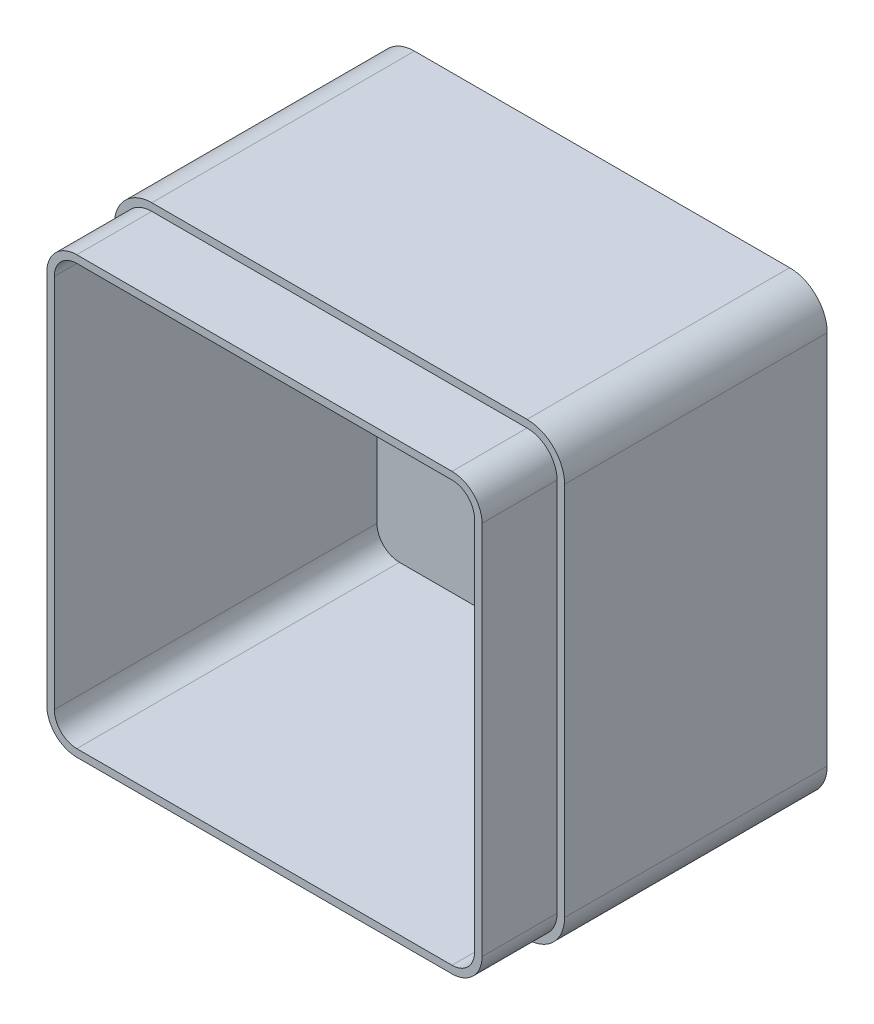
SolidWorks part; units mm, degrees
ref_plane "Front Plane" through (0, 0, 0) normal (0, 0, 1) x (1, 0, 0)
ref_plane "Top Plane" through (0, 0, 0) normal (0, 1, 0) x (1, 0, 0)
ref_plane "Right Plane" through (0, 0, 0) normal (1, 0, 0) x (0, 0, -1)
sketch "Sketch1" plane through (0, 0, 0) normal (0, 0, 1) x (1, 0, 0)
  line L1 (0, 0) -> (120, 0)
  line L2 (0, 0) -> (0, 120)
  line L3 (0, 120) -> (120, 120)
  line L4 (120, 0) -> (120, 120)
  dimension "D1" = 120
  dimension "D2" = 120
extrude "Boss-Extrude1" add sketch "Sketch1" along normal blind 90
fillet "Fillet1" radius 10 4 edges at (0, 120, 45) (0, 0, 45) (120, 0, 45) (120, 120, 45)
shell "Shell1" thickness 4
sketch "Sketch2" plane through (0, 0, 90) normal (0, 0, 1) x (1, 0, 0)
  line L0 (110, 118) -> (10, 118)
  line L1 (2, 110) -> (2, 10)
  line L2 (10, 2) -> (110, 2)
  line L3 (118, 10) -> (118, 110)
  line L4 (110, 120) -> (10, 120)
  line L5 (0, 110) -> (0, 10)
  line L6 (10, 0) -> (110, 0)
  line L7 (120, 10) -> (120, 110)
  line L8 (110, 120) -> (10, 120)
  line L9 (0, 110) -> (0, 10)
  line L10 (10, 0) -> (110, 0)
  line L11 (120, 10) -> (120, 110)
  arc A0 (10, 118) -> (2, 110) centre (10, 110) ccw
  arc A1 (2, 10) -> (10, 2) centre (10, 10) ccw
  arc A2 (110, 2) -> (118, 10) centre (110, 10) ccw
  arc A3 (118, 110) -> (110, 118) centre (110, 110) ccw
  arc A4 (10, 120) -> (0, 110) centre (10, 110) ccw
  arc A5 (0, 10) -> (10, 0) centre (10, 10) ccw
  arc A6 (110, 0) -> (120, 10) centre (110, 10) ccw
  arc A7 (120, 110) -> (110, 120) centre (110, 110) ccw
  arc A8 (10, 120) -> (0, 110) centre (10, 110) ccw
  arc A9 (0, 10) -> (10, 0) centre (10, 10) ccw
  arc A10 (110, 0) -> (120, 10) centre (110, 10) ccw
  arc A11 (120, 110) -> (110, 120) centre (110, 110) ccw
  dimension "D1" = 0
  dimension "D2" = 2
extrude "Cut-Extrude1" cut sketch "Sketch2" against normal blind 20
